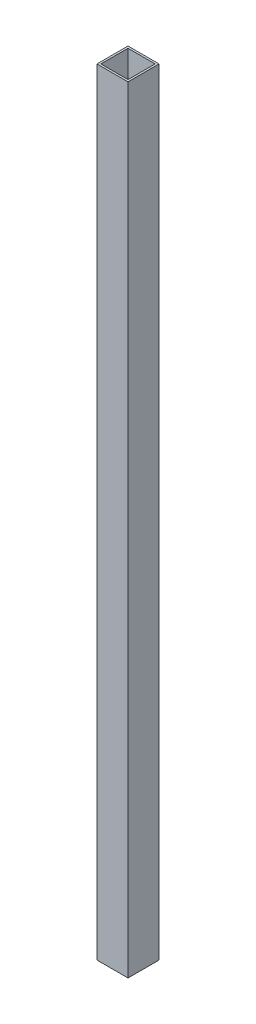
SolidWorks part; units mm, degrees
ref_plane "Front Plane" through (0, 0, 0) normal (0, 0, 1) x (1, 0, 0)
ref_plane "Top Plane" through (0, 0, 0) normal (0, 1, 0) x (1, 0, 0)
ref_plane "Right Plane" through (0, 0, 0) normal (1, 0, 0) x (0, 0, -1)
sketch "Sketch1" plane through (0, 0, 0) normal (0, 1, 0) x (1, 0, 0)
  line L1 (12.7, 12.7) -> (-12.7, 12.7)
  line L2 (12.7, 12.7) -> (12.7, -12.7)
  line L3 (12.7, -12.7) -> (-12.7, -12.7)
  line L4 (-12.7, 12.7) -> (-12.7, -12.7)
  line L5 (12.7, 12.7) -> (-12.7, -12.7) construction
  line L6 (12.7, -12.7) -> (-12.7, 12.7) construction
  line L7 (11.1125, 11.1125) -> (-11.1125, 11.1125)
  line L8 (11.1125, 11.1125) -> (11.1125, -11.1125)
  line L9 (11.1125, -11.1125) -> (-11.1125, -11.1125)
  line L10 (-11.1125, 11.1125) -> (-11.1125, -11.1125)
  line L11 (11.1125, 11.1125) -> (-11.1125, -11.1125) construction
  line L12 (11.1125, -11.1125) -> (-11.1125, 11.1125) construction
  point P0 (0, 0)
  point P6 (0, 0)
  dimension "D1" = 25.4
  dimension "D2" = 25.4
  dimension "D3" = 1.5875
  dimension "D4" = 1.5875
extrude "Boss-Extrude1" add sketch "Sketch1" along normal blind 635
